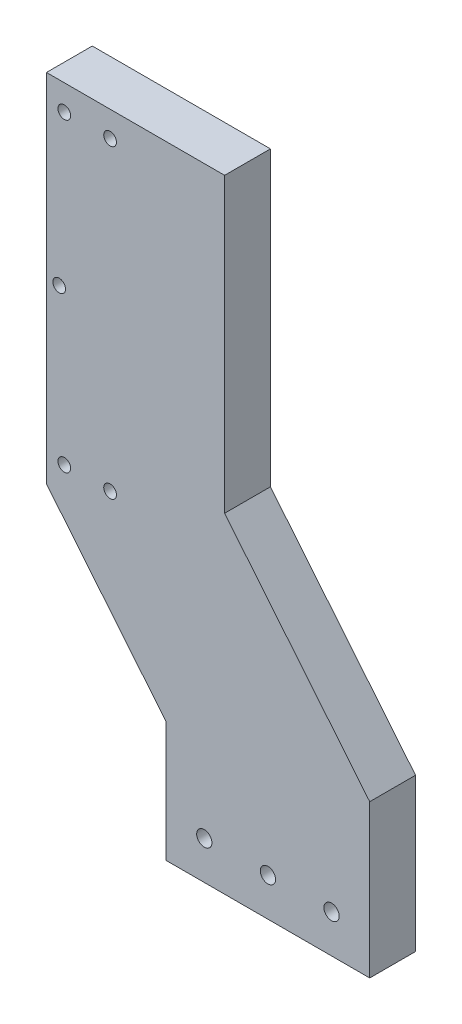
SolidWorks part; units mm, degrees
ref_plane "前视基准面" through (0, 0, 0) normal (0, 0, 1) x (1, 0, 0)
ref_plane "上视基准面" through (0, 0, 0) normal (0, 1, 0) x (1, 0, 0)
ref_plane "右视基准面" through (0, 0, 0) normal (1, 0, 0) x (0, 0, -1)
other "Configuration Table"
sketch "草图1" plane through (0, 0, 0) normal (0, 0, 1) x (1, 0, 0)
  line L0 (0, 0) -> (80, 0)
  line L2 (22.9864, 129.638) -> (22.9864, 244.638)
  line L5 (80, 0) -> (80, 60)
  line L6 (80, 60) -> (22.9864, 129.638)
  line L7 (0, 0) -> (0, 47.2143)
  line L8 (0, 47.2143) -> (-47.0136, 104.638)
  line L9 (-47.0136, 104.638) -> (-47.0136, 244.638)
  line L11 (-47.0136, 244.638) -> (22.9864, 244.638)
  dimension "D1" = 80
  dimension "D2" = 115
  dimension "D3" = 140
  dimension "D4" = 70
  dimension "D5" = 60
  dimension "D6" = 70
  dimension "D7" = 90
extrude "凸台-拉伸1" add sketch "草图1" along normal blind 18 contours L0 L5 L6 L2 L11 L9 L8 L7
sketch "草图2" plane through (0, 0, 18) normal (0, 0, 1) x (1, 0, 0)
  line L0 (-47.0136, 104.638) -> (-47.0136, 244.638) construction
  line L1 (-47.0136, 244.638) -> (22.9864, 244.638) construction
  line L2 (-47.0136, 174.638) -> (9.6331, 174.638) construction
  circle A0 centre (-40.0136, 234.638) radius 4
  circle A1 centre (-22.0136, 234.638) radius 4
  circle A2 centre (-22.0136, 114.638) radius 4
  circle A3 centre (-40.0136, 114.638) radius 4
  dimension "D1" = 8
  dimension "D2" = 8
  dimension "D3" = 18
  dimension "D4" = 7
  dimension "D5" = 10
sketch "草图5" plane through (0, 0, 18) normal (0, 0, 1) x (1, 0, 0)
  line L2 (-47.0136, 174.638) -> (9.6331, 174.638) construction
  line L3 (-47.0136, 104.638) -> (-47.0136, 244.638) construction
  circle A2 centre (-42.0136, 174.638) radius 3
  dimension "D1" = 6
  dimension "D2" = 5
hole_wizard "M6 螺纹孔1" positions "草图4" profile "草图3" tap size "M6" standard "GB" end condition through all
sketch "草图4" plane through (0, 0, 18) normal (0, 0, 1) x (1, 0, 0)
  point P31 (-40.0136, 114.638)
  point P34 (-22.0136, 114.638)
  point P37 (-40.0136, 234.638)
  point P40 (-22.0136, 234.638)
sketch "草图3" plane through (-40.0136, 114.638, 18) normal (1, 0, 0) x (0, -1, 0)
  line L0 (0, 0) -> (0, 18)
  line L1 (0, 18) -> (2.5, 18)
  line L2 (2.5, 18) -> (2.5, 0)
  line L5 (2.5, 0) -> (0, 0)
  line L11 (0, -6.35) -> (0, 107.95) construction
  dimension "通孔螺纹孔钻头直径" = 5
  dimension "通孔螺纹孔钻头深度" = 18
cosmetic thread "孔螺蚊线1" parameters "D2"=6
cosmetic thread "孔螺蚊线2" parameters "D2"=6
cosmetic thread "孔螺蚊线7" parameters "D2"=6
cosmetic thread "孔螺蚊线8" parameters "D2"=6
sketch "草图7" plane through (0, 0, 18) normal (0, 0, 1) x (1, 0, 0)
  circle A0 centre (15, 15) radius 3
  circle A1 centre (40, 15) radius 3
  circle A2 centre (65, 15) radius 3
  dimension "D1" = 6
  dimension "D2" = 6
  dimension "D3" = 6
extrude "切除-拉伸1" cut sketch "草图7" against normal through all
hole_wizard "M6 螺纹孔2" positions "3D草图1" profile "草图8" tap size "M6" standard "GB" end condition through all
sketch3d "3D草图1"
  point P0 (-42.0136, 174.638, 18)
sketch "草图8" plane through (-42.0136, 174.638, 18) normal (1, 0, 0) x (0, -1, 0)
  line L0 (0, 0) -> (0, 18)
  line L1 (0, 18) -> (2.5, 18)
  line L2 (2.5, 18) -> (2.5, 0)
  line L5 (2.5, 0) -> (0, 0)
  line L11 (0, -6.35) -> (0, 107.95) construction
  dimension "通孔螺纹孔钻头直径" = 5
  dimension "通孔螺纹孔钻头深度" = 18
cosmetic thread "孔螺蚊线9" parameters "D2"=6
